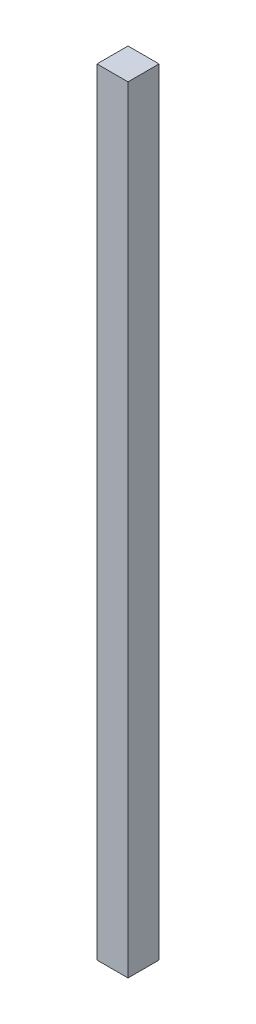
SolidWorks part; units mm, degrees
ref_plane "Ebene vorne" through (0, 0, 0) normal (0, 0, 1) x (1, 0, 0)
ref_plane "Ebene oben" through (0, 0, 0) normal (0, 1, 0) x (1, 0, 0)
ref_plane "Ebene rechts" through (0, 0, 0) normal (1, 0, 0) x (0, 0, -1)
sketch "Skizze1" plane through (0, 0, 0) normal (0, 0, 1) x (1, 0, 0)
  line L1 (0, 0) -> (40, 0)
  line L2 (0, 0) -> (0, 1000)
  line L3 (0, 1000) -> (40, 1000)
  line L4 (40, 0) -> (40, 1000)
  dimension "D1" = 1000
  dimension "D2" = 40
extrude "Aufsatz-Linear austragen1" add sketch "Skizze1" along normal blind 40
